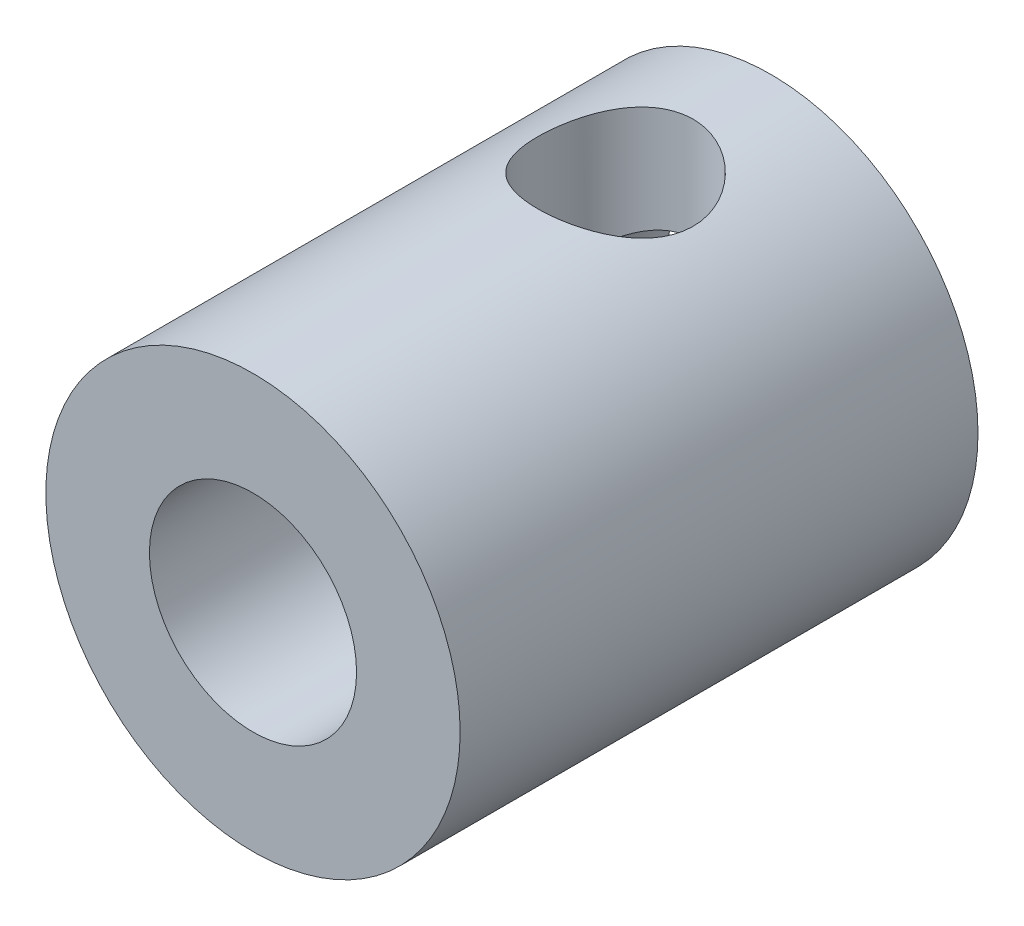
SolidWorks part; units mm, degrees
ref_plane "前视基准面" through (0, 0, 0) normal (0, 0, 1) x (1, 0, 0)
ref_plane "上视基准面" through (0, 0, 0) normal (0, 1, 0) x (1, 0, 0)
ref_plane "右视基准面" through (0, 0, 0) normal (1, 0, 0) x (0, 0, -1)
sketch "草图1" plane through (0, 0, 0) normal (0, 0, 1) x (1, 0, 0)
  circle A0 centre (0, 0) radius 10
  circle A1 centre (0, 0) radius 20
  dimension "D1" = 20
  dimension "D2" = 40
extrude "凸台-拉伸1" add sketch "草图1" along normal blind 50
sketch "草图2" plane through (0, 0, 0) normal (0, 1, 0) x (1, 0, 0)
  line L0 (0, 0) -> (0, -15) construction
  circle A0 centre (0, -15) radius 7.5
  dimension "D2" = 15
  dimension "D1" = 15
extrude "切除-拉伸1" cut sketch "草图2" along normal blind 30
